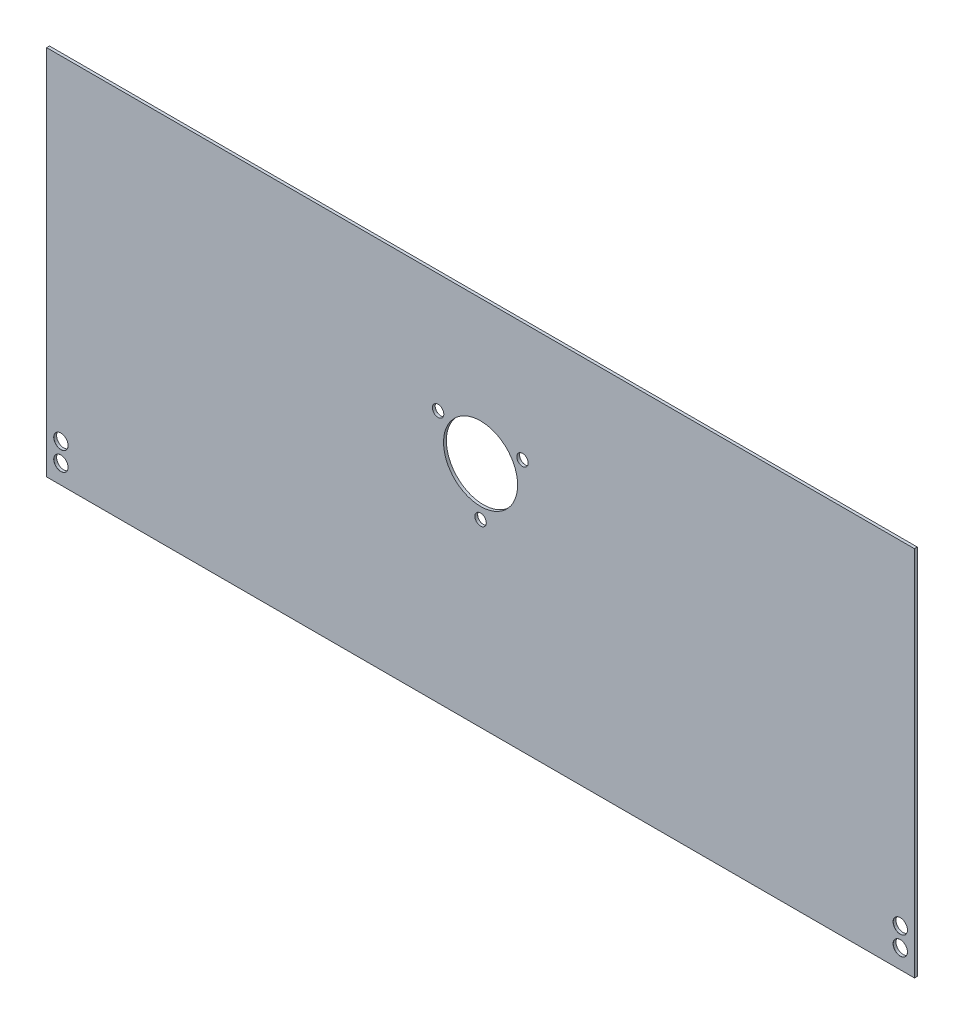
SolidWorks part; units mm, degrees
ref_plane "Front Plane" through (0, 0, 0) normal (0, 0, 1) x (1, 0, 0)
ref_plane "Top Plane" through (0, 0, 0) normal (0, 1, 0) x (1, 0, 0)
ref_plane "Right Plane" through (0, 0, 0) normal (1, 0, 0) x (0, 0, -1)
sketch "Sketch1" plane through (0, 0, 0) normal (0, 0, 1) x (1, 0, 0)
  line L0 (0, 0) -> (14.7224, 8.5)
  line L1 (0, 0) -> (0, -17)
  line L2 (0, 0) -> (-14.7224, 8.5)
  line L3 (0, 0) -> (0, -80.25)
  line L4 (-152.4, -80.25) -> (152.4, -80.25)
  line L5 (0, 40.25) -> (0, 50.25)
  line L6 (0, -80.25) -> (0, -40.25)
  line L8 (-152.4, -80.25) -> (152.4, -80.25)
  line L9 (-152.4, -80.25) -> (-152.4, -76.75)
  line L10 (-152.4, -76.75) -> (152.4, -76.75)
  line L11 (152.4, -80.25) -> (152.4, -76.75)
  line L12 (-152.4, -76.75) -> (-142.4, -76.75)
  line L13 (-152.4, -76.75) -> (-152.4, -60.25)
  line L14 (-152.4, -60.25) -> (-142.4, -60.25)
  line L15 (-142.4, -76.75) -> (-142.4, -60.25)
  line L16 (152.4, -76.75) -> (142.4, -76.75)
  line L17 (152.4, -76.75) -> (152.4, -60.25)
  line L18 (152.4, -60.25) -> (142.4, -60.25)
  line L19 (142.4, -76.75) -> (142.4, -60.25)
  circle A0 centre (0, 0) radius 13.01
  circle A1 centre (0, 0) radius 17
  circle A2 centre (0, -17) radius 2.01
  circle A3 centre (14.7506, 8.5319) radius 2.01
  circle A4 centre (-14.9188, 8.588) radius 2.01
  circle A5 centre (0, 0) radius 40.25
  arc A6 (-152.4, -60.25) -> (152.4, -60.25) centre (0, -109.9718) cw
  point P16 (0, -80.25)
  dimension "D1" = 26.02
  dimension "D2" = 34
  dimension "D3" = 4.02
  dimension "D8" = 80.5
  dimension "D4" = 120
  dimension "D5" = 120
  dimension "D6" = 80.25
  dimension "D7" = 304.8
  dimension "D9" = 3.5
  dimension "D10" = 10
  dimension "D11" = 10
  dimension "D12" = 16.5
  dimension "D13" = 16.5
  dimension "D14" = 10
extrude "Boss-Extrude2" add sketch "Sketch1" along normal blind 1
sketch "Sketch7" plane through (0, 0, 1) normal (0, 0, 1) x (1, 0, 0)
  line L0 (-142.4, -76.75) -> (-152.4, -76.75) construction
  line L1 (-142.4, -60.25) -> (-152.4, -60.25) construction
  line L2 (-147.4, -80.25) -> (-147.4, -73.5833)
  line L3 (-152.4, -80.25) -> (152.4, -80.25) construction
  line L4 (-147.4, -73.5833) -> (-147.4, -66.9167)
  line L5 (0, -80.25) -> (0, -40.25)
  line L6 (147.4, -80.25) -> (147.4, -73.5833)
  line L7 (147.4, -73.5833) -> (147.4, -66.9167)
  dimension "D1" = 6.6667
  dimension "D2" = 6.6667
hole_wizard "Ø5.0mm Dowel Hole4" positions "Sketch8" profile "Sketch9" hole size "Ø5.0" standard "ANSI Metric"
sketch "Sketch8" plane through (0, 0, 1) normal (0, 0, 1) x (1, 0, 0)
  point P0 (-147.4, -66.9167)
  point P3 (-147.4, -73.5833)
  point P6 (147.4, -66.9167)
  point P9 (147.4, -73.5833)
sketch "Sketch9" plane through (-147.4, -66.9167, 1) normal (1, 0, 0) x (0, -1, 0)
  line L0 (0, 0) -> (0, 2.5022)
  line L1 (0, 2.5022) -> (2.5, 1)
  line L2 (2.5, 1) -> (2.5, 0.025)
  line L3 (2.5, 0.025) -> (2.525, 0)
  line L5 (2.525, 0) -> (0, 0)
  line L6 (-2.5, 0.025) -> (-2.525, 0) construction
  line L10 (0, 2.5022) -> (-2.5, 1) construction
  line L11 (0, -6.35) -> (0, 107.95) construction
  dimension "Hole Dia." = 5
  dimension "Hole Depth" = 1
  dimension "Near C'Sink Dia." = 5.05
  dimension "Near C'Sink Angle" = 90
  dimension "Drill Angle" = 118
sketch "Sketch10" plane through (0, 0, 1) normal (0, 0, 1) x (1, 0, 0)
  point P0 (-14.9188, 8.588)
  point P1 (14.7224, 8.5)
  point P3 (0, -17)
hole_wizard "Ø4.0mm Dowel Hole1" positions "Sketch12" profile "Sketch13" hole size "Ø4.0" standard "ANSI Metric" end condition through all
sketch "Sketch12" plane through (0, 0, 0) normal (0, 0, -1) x (-1, 0, 0)
  point P0 (14.9188, 8.588)
  point P3 (-14.7224, 8.5)
  point P6 (0, -17)
sketch "Sketch13" plane through (-14.9188, 8.588, 0) normal (1, 0, 0) x (0, 1, 0)
  line L0 (0, 0) -> (0, 1)
  line L1 (0, 1) -> (2, 1)
  line L2 (2, 1) -> (2, 0.025)
  line L3 (2, 0.025) -> (2.025, 0)
  line L5 (2.025, 0) -> (0, 0)
  line L6 (-2, 0.025) -> (-2.025, 0) construction
  line L11 (0, -6.35) -> (0, 107.95) construction
  dimension "Thru Hole Dia." = 4
  dimension "Thru Hole Depth" = 1
  dimension "Near C'Sink Dia." = 4.05
  dimension "Near C'Sink Angle" = 90
sketch "Sketch14" plane through (0, 0, 0) normal (0, 0, -1) x (-1, 0, 0)
  circle A0 centre (0, 0) radius 13.01
extrude "Cut-Extrude1" cut sketch "Sketch14" against normal blind 10
sketch "Sketch15" plane through (0, 0, 0) normal (0, 0, -1) x (-1, 0, 0)
  line L1 (-152.4, -60.25) -> (152.4, -60.25)
  line L2 (-152.4, -60.25) -> (-152.4, 50.3342)
  line L3 (-152.4, 50.3342) -> (152.4, 50.3342)
  line L4 (152.4, -60.25) -> (152.4, 50.3342)
  arc A0 (-152.4, -60.25) -> (152.4, -60.25) centre (0, -125.6296) cw
  arc M9 (152.4, -60.25) -> (-152.4, -60.25) centre (0, -109.9718) ccw
extrude "Boss-Extrude4" add sketch "Sketch15" against normal blind 1 contours A0 M9 | L3 L2 M9 | L4 L3 M9
equation "\"127.80063128mmftft\"=127.801"
